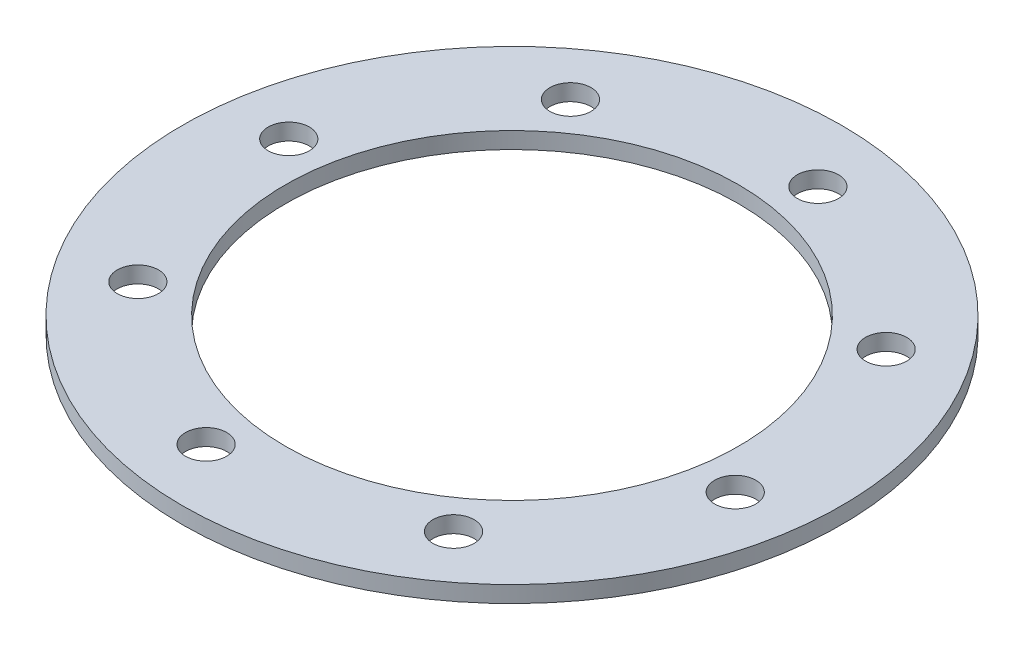
SolidWorks part; units mm, degrees
ref_plane "前视基准面" through (0, 0, 0) normal (0, 0, 1) x (1, 0, 0)
ref_plane "上视基准面" through (0, 0, 0) normal (0, 1, 0) x (1, 0, 0)
ref_plane "右视基准面" through (0, 0, 0) normal (1, 0, 0) x (0, 0, -1)
other "Configuration Table"
sketch "草图1" plane through (0, 0, 0) normal (0, 1, 0) x (1, 0, 0)
  circle A0 centre (0, 0) radius 27.5
  circle A1 centre (0, 0) radius 40
  dimension "D1" = 55
  dimension "D2" = 80
extrude "凸台-拉伸1" add sketch "草图1" along normal blind 2
sketch "草图2" plane through (0, 0, 0) normal (0, -1, 0) x (1, 0, 0)
  arc A2 (-32.4963, -2.5471) -> (-31.7245, -7.4872) centre (-32.1104, -5.0171) ccw
  arc A3 (-31.7245, -7.4872) -> (-32.4963, -2.5471) centre (-32.1104, -5.0171) ccw
  arc A4 (-32.4963, -2.5471) -> (-31.7245, -7.4872) centre (-32.1104, -5.0171) ccw
  arc A5 (-31.7245, -7.4872) -> (-32.4963, -2.5471) centre (-32.1104, -5.0171) ccw
  arc A6 (-26.6391, 21.6279) -> (-25.8672, 16.6878) centre (-26.2531, 19.1578) ccw
  arc A7 (-25.8672, 16.6878) -> (-26.6391, 21.6279) centre (-26.2531, 19.1578) ccw
  arc A8 (-26.6391, 21.6279) -> (-25.8672, 16.6878) centre (-26.2531, 19.1578) ccw
  arc A9 (-25.8672, 16.6878) -> (-26.6391, 21.6279) centre (-26.2531, 19.1578) ccw
  arc A10 (-5.4031, 34.5804) -> (-4.6312, 29.6404) centre (-5.0171, 32.1104) ccw
  arc A11 (-4.6312, 29.6404) -> (-5.4031, 34.5804) centre (-5.0171, 32.1104) ccw
  arc A12 (-5.4031, 34.5804) -> (-4.6312, 29.6404) centre (-5.0171, 32.1104) ccw
  arc A13 (-4.6312, 29.6404) -> (-5.4031, 34.5804) centre (-5.0171, 32.1104) ccw
  arc A14 (18.7719, 28.7232) -> (19.5438, 23.7831) centre (19.1578, 26.2531) ccw
  arc A15 (19.5438, 23.7831) -> (18.7719, 28.7232) centre (19.1578, 26.2531) ccw
  arc A16 (18.7719, 28.7232) -> (19.5438, 23.7831) centre (19.1578, 26.2531) ccw
  arc A17 (19.5438, 23.7831) -> (18.7719, 28.7232) centre (19.1578, 26.2531) ccw
  arc A18 (31.7245, 7.4872) -> (32.4963, 2.5471) centre (32.1104, 5.0171) ccw
  arc A19 (32.4963, 2.5471) -> (31.7245, 7.4872) centre (32.1104, 5.0171) ccw
  arc A20 (31.7245, 7.4872) -> (32.4963, 2.5471) centre (32.1104, 5.0171) ccw
  arc A21 (32.4963, 2.5471) -> (31.7245, 7.4872) centre (32.1104, 5.0171) ccw
  arc A22 (25.8672, -16.6878) -> (26.6391, -21.6279) centre (26.2531, -19.1578) ccw
  arc A23 (26.6391, -21.6279) -> (25.8672, -16.6878) centre (26.2531, -19.1578) ccw
  arc A24 (25.8672, -16.6878) -> (26.6391, -21.6279) centre (26.2531, -19.1578) ccw
  arc A25 (26.6391, -21.6279) -> (25.8672, -16.6878) centre (26.2531, -19.1578) ccw
  arc A26 (-19.5438, -23.7831) -> (-18.7719, -28.7232) centre (-19.1578, -26.2531) ccw
  arc A27 (-18.7719, -28.7232) -> (-19.5438, -23.7831) centre (-19.1578, -26.2531) ccw
  arc A28 (-19.5438, -23.7831) -> (-18.7719, -28.7232) centre (-19.1578, -26.2531) ccw
  arc A29 (-18.7719, -28.7232) -> (-19.5438, -23.7831) centre (-19.1578, -26.2531) ccw
  arc A30 (4.6312, -29.6404) -> (5.4031, -34.5804) centre (5.0171, -32.1104) ccw
  arc A31 (5.4031, -34.5804) -> (4.6312, -29.6404) centre (5.0171, -32.1104) ccw
  arc A32 (4.6312, -29.6404) -> (5.4031, -34.5804) centre (5.0171, -32.1104) ccw
  arc A33 (5.4031, -34.5804) -> (4.6312, -29.6404) centre (5.0171, -32.1104) ccw
  dimension "D1" = 0
  dimension "D2" = 0
  dimension "D3" = 0
  dimension "D4" = 0
  dimension "D5" = 0
  dimension "D6" = 0
  dimension "D7" = 0
  dimension "D8" = 0
extrude "切除-拉伸1" cut sketch "草图2" against normal blind 5
